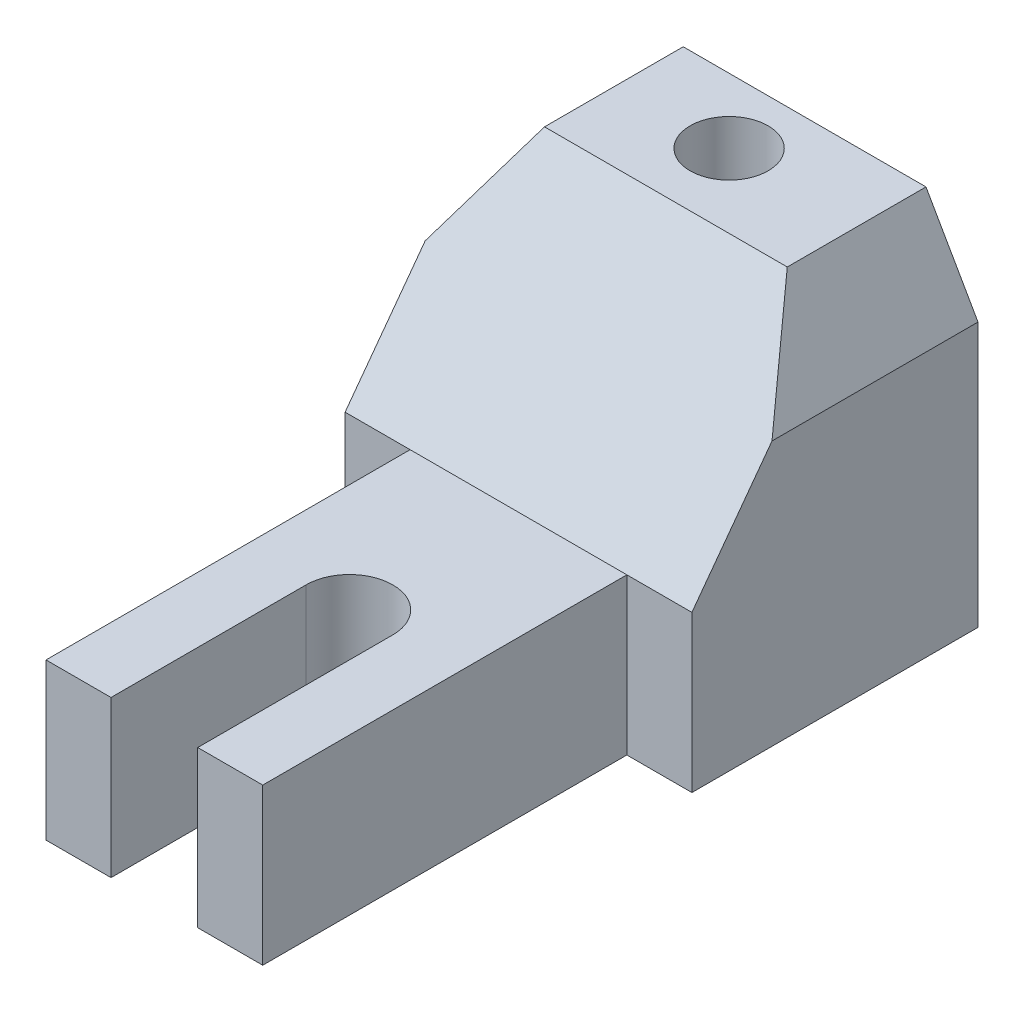
SolidWorks part; units mm, degrees
ref_plane "Front Plane" through (0, 0, 0) normal (0, 0, 1) x (1, 0, 0)
ref_plane "Top Plane" through (0, 0, 0) normal (0, 1, 0) x (1, 0, 0)
ref_plane "Right Plane" through (0, 0, 0) normal (1, 0, 0) x (0, 0, -1)
sketch "Sketch1" plane through (0, 0, 0) normal (1, 0, 0) x (0, 0, -1)
  line L0 (-44.1719, 0) -> (-44.1719, 36)
  line L1 (-44.1719, 36) -> (-10.1719, 82)
  line L2 (-10.1719, 82) -> (21.8281, 82)
  line L3 (21.8281, 82) -> (21.8281, 0)
  line L4 (21.8281, 0) -> (-44.1719, 0)
  dimension "D1" = 66
  dimension "D2" = 82
  dimension "D3" = 36
  dimension "D4" = 32
extrude "Boss-Extrude1" add sketch "Sketch1" against normal blind 80
fillet "Chamfer1" radius 12 1 edges at (0, 82, -5.8281) profile chamfer
fillet "Chamfer2" radius 21 1 edges at (-80, 82, -5.8281)
sketch "Sketch2" plane through (0, 82, 0) normal (0, 1, 0) x (1, 0, 0)
  line L0 (-68, 21.8281) -> (-12, 21.8281) construction
  line L1 (-68, -10.1719) -> (-12, -10.1719) construction
  line L3 (0, -25.6936) -> (0, -44.1719) construction
  line L4 (-80, -25.6936) -> (-80, -44.1719) construction
  circle A0 centre (-42.4156, 6.8281) radius 9
  dimension "D1" = 15
  dimension "D2" = 32
  dimension "D3" = 80
extrude "Cut-Extrude1" cut sketch "Sketch2" against normal blind 80
sketch "Sketch3" plane through (0, 0, 0) normal (0, -1, 0) x (1, 0, 0)
  line L0 (-80, 44.1719) -> (0, 44.1719) construction
  line L1 (-65, 44.1719) -> (-15, 44.1719)
  line L2 (-65, 44.1719) -> (-65, 128.1719)
  line L3 (-65, 128.1719) -> (-15, 128.1719)
  line L4 (-15, 44.1719) -> (-15, 128.1719)
  line L5 (-80, 44.1719) -> (-65, 44.1719)
  line L6 (-15, 44.1719) -> (0, 44.1719)
  line L7 (-40, 128.1719) -> (-40, 83.1719) construction
  line L10 (-30, 128.1719) -> (-30, 83.1719)
  line L11 (-50, 128.1719) -> (-50, 83.1719)
  arc A2 (-30, 128.1719) -> (-50, 128.1719) centre (-40, 128.1719) ccw
  arc A3 (-50, 83.1719) -> (-30, 83.1719) centre (-40, 83.1719) ccw
  point P12 (-40, 105.6719)
  line M14 (0, 44.1719) -> (-80, 44.1719)
  dimension "D5" = 10
  dimension "D1" = 84
  dimension "D2" = 50
  dimension "D3" = 15
  dimension "D4" = 45
extrude "Boss-Extrude2" add sketch "Sketch3" against normal blind 36 contours A3 L11 L3 L2 L4 L10 M14
